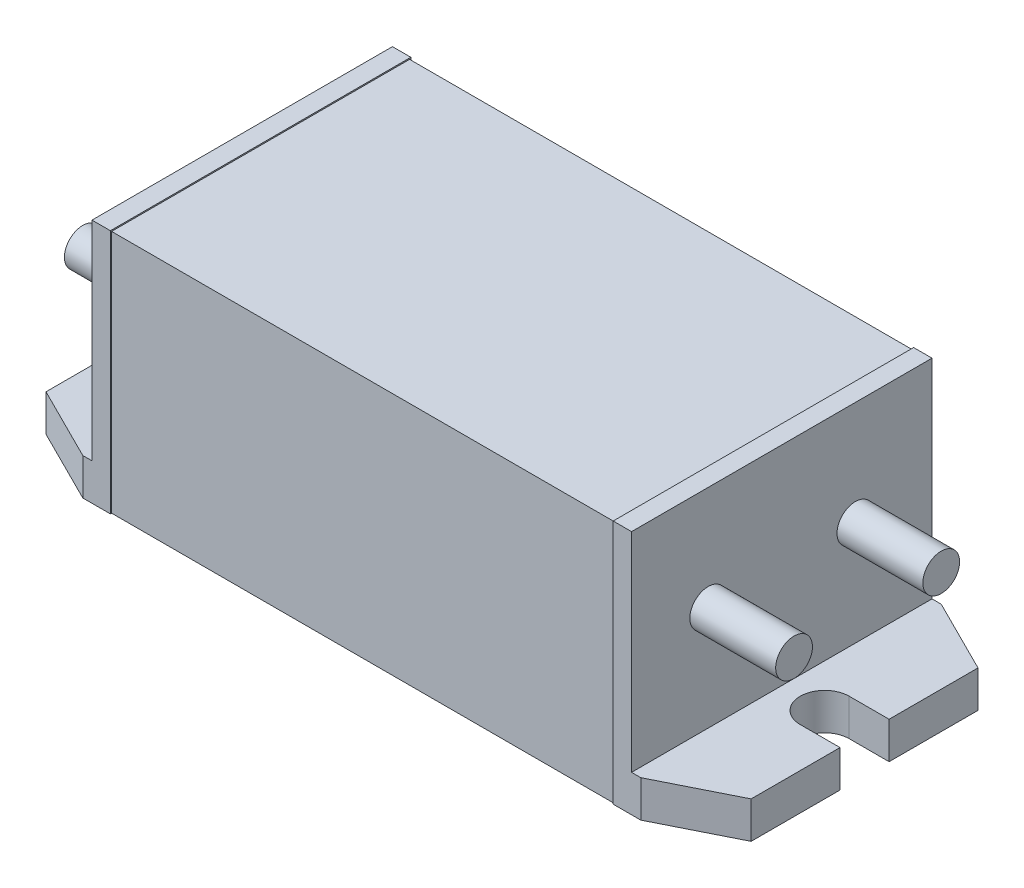
SolidWorks part; units mm, degrees
ref_plane "前视基准面" through (0, 0, 0) normal (0, 0, 1) x (1, 0, 0)
ref_plane "上视基准面" through (0, 0, 0) normal (0, 1, 0) x (1, 0, 0)
ref_plane "右视基准面" through (0, 0, 0) normal (1, 0, 0) x (0, 0, -1)
sketch "草图1" plane through (0, 0, 0) normal (0, 1, 0) x (1, 0, 0)
  line L1 (22, -12.25) -> (-22, -12.25)
  line L2 (22, -12.25) -> (22, 12.25)
  line L3 (22, 12.25) -> (-22, 12.25)
  line L4 (-22, -12.25) -> (-22, 12.25)
  line L5 (22, -12.25) -> (-22, 12.25) construction
  line L6 (22, 12.25) -> (-22, -12.25) construction
  point P0 (0, 0)
  dimension "D1" = 44
  dimension "D2" = 24.5
extrude "凸台-拉伸1" add sketch "草图1" along normal blind 20
sketch "草图2" plane through (0, 0, 0) normal (0, -1, 0) x (1, 0, 0)
  line L0 (-22, 12.25) -> (22, 12.25) construction
  line L1 (28.75, -12.25) -> (-28.75, -12.25)
  line L2 (28.75, -12.25) -> (28.75, 12.25)
  line L3 (28.75, 12.25) -> (-28.75, 12.25)
  line L4 (-28.75, -12.25) -> (-28.75, 12.25)
  line L5 (28.75, -12.25) -> (-28.75, 12.25) construction
  line L6 (28.75, 12.25) -> (-28.75, -12.25) construction
  point P0 (0, 0)
  dimension "D1" = 57.5
extrude "凸台-拉伸2" add sketch "草图2" against normal blind 3
chamfer "倒角1" distance 3 distance2 6 2 edges at (28.75, 1.5, -12.25) (-28.75, 1.5, 12.25)
chamfer "倒角2" distance 6 distance2 3 2 edges at (28.75, 1.5, 12.25) (-28.75, 1.5, -12.25)
sketch "草图3" plane through (0, 3, 0) normal (0, 1, 0) x (1, 0, 0)
  line L0 (0, 0) -> (0, 9.4102) construction
  line L1 (-28.75, -9.25) -> (-28.75, 9.25) construction
  line L2 (-22.25, -2) -> (-28.75, -2) construction
  line L3 (-22.25, -2) -> (-22.25, 2) construction
  line L4 (-25.5, 2) -> (-28.75, 2)
  line L5 (-28.75, -2) -> (-28.75, 2)
  line L6 (-22.25, -2) -> (-28.75, 2) construction
  line L7 (-22.25, 2) -> (-28.75, -2) construction
  line L8 (-28.75, -2) -> (-25.5, -2)
  line L9 (28.75, -2) -> (25.5, -2)
  line L10 (28.75, -2) -> (28.75, 2)
  line L11 (25.5, 2) -> (28.75, 2)
  arc A0 (-25.5, -2) -> (-25.5, 2) centre (-25.5, 0) ccw
  circle A1 centre (25.5, 0) radius 2 construction
  arc A2 (25.5, -2) -> (25.5, 2) centre (25.5, 0) cw
  point P1 (-27.125, -2)
  point P15 (27.125, -2)
  dimension "D1" = 4
  dimension "D2" = 51
extrude "切除-拉伸1" cut sketch "草图3" against normal through all
sketch "草图4" plane through (-22, 0, 0) normal (-1, 0, 0) x (0, 0, 1)
  line L0 (0, 20) -> (0, 3) construction
  line L1 (-12.25, 20) -> (12.25, 20) construction
  line L2 (2, 3) -> (-2, 3) construction
  circle A0 centre (-6, 11.5) radius 1.5
  circle A1 centre (6, 11.5) radius 1.5
  point P9 (0, 11.5)
  dimension "D1" = 3
  dimension "D2" = 6
extrude "凸台-拉伸3" add sketch "草图4" along normal blind 7
ref_plane "基准面1" through (0, 0, 0) normal (-1, 0, 0) x (0, 0, 1)
mirror "镜向1" about plane through (0, 0, 0) normal (-1, 0, 0) of "凸台-拉伸3"
sketch "草图5" plane through (0, 0, 0) normal (1, 0, 0) x (0, 0, -1)
  line L1 (12.25, 20) -> (12.25, 3) construction
  line L2 (-12.25, 20) -> (12.25, 20) construction
  line L3 (-12.25, 20) -> (-12.25, 3) construction
  line L4 (-12.25, 3) -> (-12.25, 0)
  line L5 (12.25, 20) -> (12.25, 3)
  line L6 (-12.25, 20) -> (12.25, 20)
  line L7 (-12.25, 20) -> (-12.25, 3)
  line L8 (-12.25, 0) -> (-12.15, 0)
  line L9 (-12.15, 19.9) -> (-12.15, 3.1)
  line L10 (-12.15, 19.9) -> (12.15, 19.9)
  line L11 (12.15, 19.9) -> (12.15, 3.1)
  line L12 (12.25, 3) -> (-12.25, 3) construction
  line L13 (12.15, 3.1) -> (-12.15, 3.1) construction
  line L14 (12.25, 0) -> (12.25, 3)
  line L15 (-9.25, 0) -> (-12.25, 0) construction
  line L16 (-12.15, 3.1) -> (-12.15, 0)
  line L17 (12.15, 3.1) -> (12.15, 0)
  line L18 (12.25, 0) -> (9.25, 0) construction
  line L19 (12.15, 0) -> (12.25, 0)
  dimension "D1" = 0.1
extrude "切除-拉伸2" cut sketch "草图5" against normal mid plane 41
